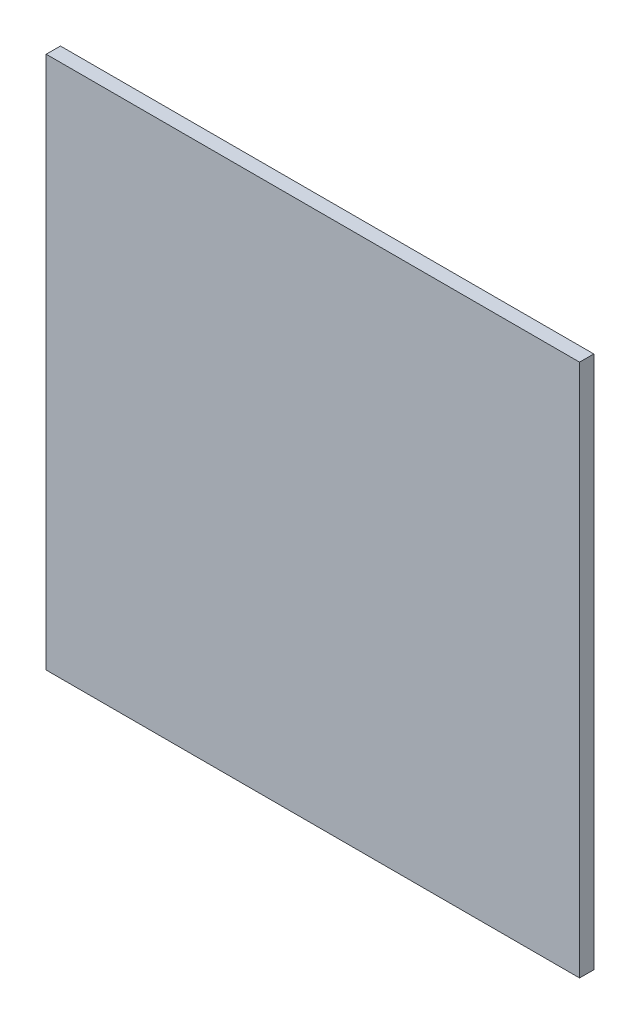
SolidWorks part; units mm, degrees
ref_plane "Front Plane" through (0, 0, 0) normal (0, 0, 1) x (1, 0, 0)
ref_plane "Top Plane" through (0, 0, 0) normal (0, 1, 0) x (1, 0, 0)
ref_plane "Right Plane" through (0, 0, 0) normal (1, 0, 0) x (0, 0, -1)
sketch "Sketch1" plane through (0, 0, 0) normal (0, 0, 1) x (1, 0, 0)
  line L1 (-15, -15) -> (15, -15)
  line L2 (-15, -15) -> (-15, 15)
  line L3 (-15, 15) -> (15, 15)
  line L4 (15, -15) -> (15, 15)
  line L5 (0, 15) -> (0, -15) construction
  line L6 (-15, 0) -> (15, 0) construction
  point P0 (0, 0)
  dimension "D1" = 30
  dimension "D2" = 30
extrude "Boss-Extrude1" add sketch "Sketch1" along normal blind 0.8
